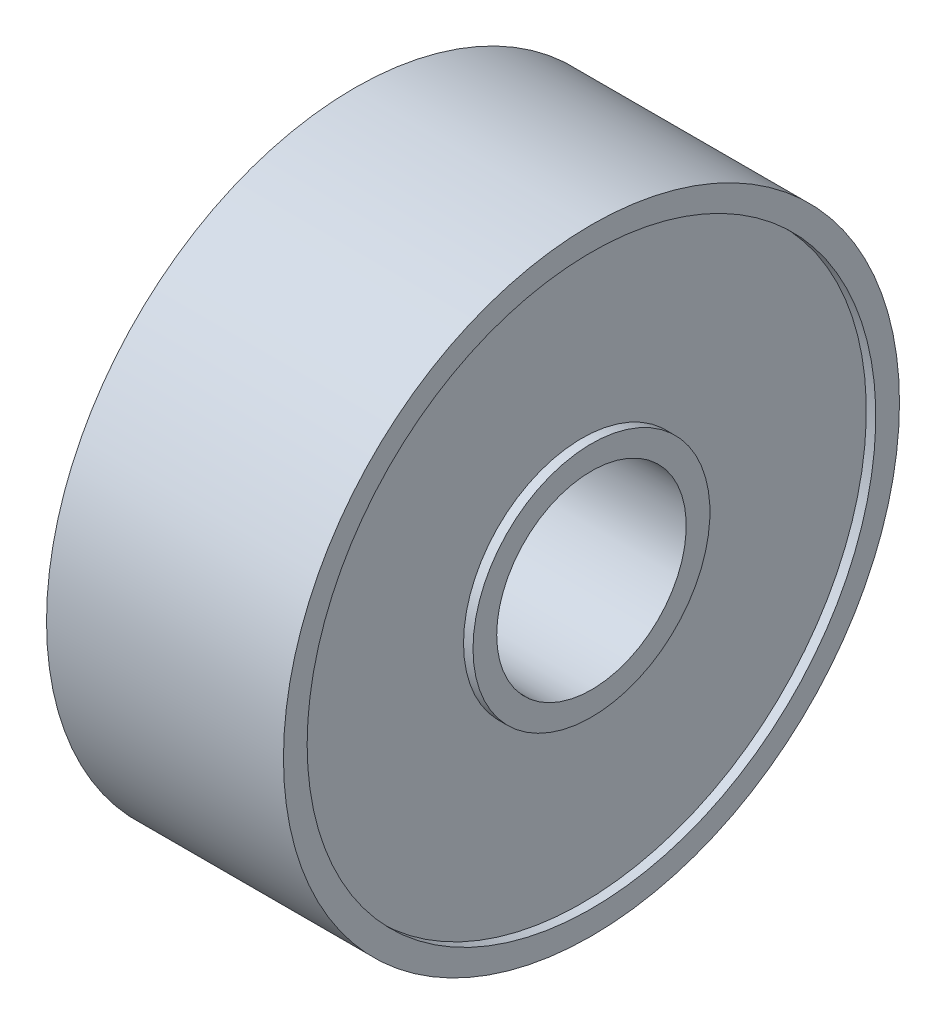
SolidWorks part; units mm, degrees
material "Acier allié"
ref_plane "Plan de face" through (0, 0, 0) normal (0, 0, 1) x (1, 0, 0)
ref_plane "Plan de dessus" through (0, 0, 0) normal (0, 1, 0) x (1, 0, 0)
ref_plane "Plan de droite" through (0, 0, 0) normal (1, 0, 0) x (0, 0, -1)
sketch "Esquisse1" plane through (0, 0, 0) normal (0, 0, 1) x (1, 0, 0)
  line L1 (-2.5, 2.5) -> (-2.3, 2.5)
  line L2 (-2.5, 2.5) -> (-2.5, 2)
  line L3 (-2.5, 2) -> (2.5, 2)
  line L4 (2.5, 2.5) -> (2.5, 2)
  line L5 (2.3, 6) -> (2.5, 6)
  line L6 (-2.3, 6) -> (-2.3, 2.5)
  line L8 (2.3, 6) -> (2.3, 2.5)
  line L9 (-2.5, 6.5) -> (2.5, 6.5)
  line L10 (-2.5, 6.5) -> (-2.5, 6)
  line L11 (-2.5, 6) -> (-2.3, 6)
  line L12 (2.5, 6.5) -> (2.5, 6)
  line L15 (-2.5, 0) -> (2.5, 0) construction
  line L16 (2.3, 2.5) -> (2.5, 2.5)
  point P18 (0, 2)
  dimension "D7" = 0.5
  dimension "D1" = 13
  dimension "D2" = 5
  dimension "D3" = 4
  dimension "D4" = 5
  dimension "D5" = 12
  dimension "D6" = 0.2
  dimension "D8" = 0.5
revolve "Révolution1" add sketch "Esquisse1" angle 360 about L15
